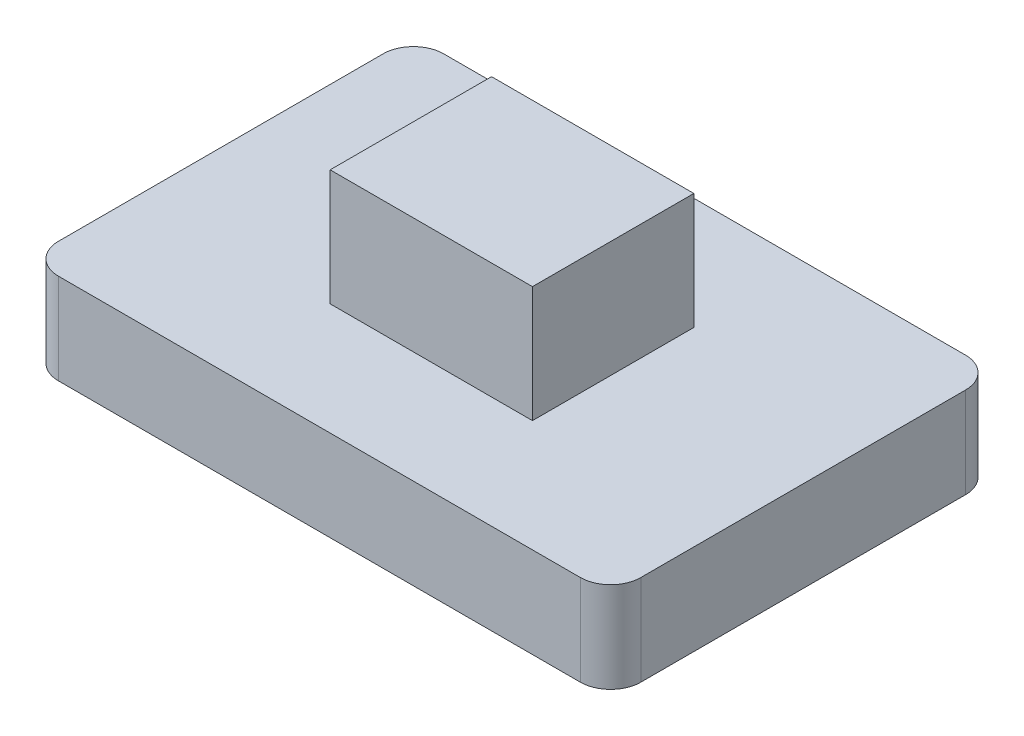
SolidWorks part; units mm, degrees
ref_plane "Front Plane" through (0, 0, 0) normal (0, 0, 1) x (1, 0, 0)
ref_plane "Top Plane" through (0, 0, 0) normal (0, 1, 0) x (1, 0, 0)
ref_plane "Right Plane" through (0, 0, 0) normal (1, 0, 0) x (0, 0, -1)
sketch "Sketch3" plane through (0, 0, 0) normal (0, 1, 0) x (1, 0, 0)
  line L1 (6.35, 0) -> (116.0039, 0)
  line L2 (0, 6.35) -> (0, 74.5793)
  line L3 (6.35, 80.9293) -> (116.0039, 80.9293)
  line L4 (122.3539, 6.35) -> (122.3539, 74.5793)
  arc A0 (6.35, 0) -> (0, 6.35) centre (6.35, 6.35) cw
  arc A1 (6.35, 80.9293) -> (0, 74.5793) centre (6.35, 74.5793) ccw
  arc A2 (122.3539, 74.5793) -> (116.0039, 80.9293) centre (116.0039, 74.5793) ccw
  arc A3 (122.3539, 6.35) -> (116.0039, 0) centre (116.0039, 6.35) cw
  point P7 (0, 0)
  dimension "D1" = 6.35
  dimension "D2" = 6.35
extrude "Extrude4" add sketch "Sketch3" against normal blind 19.05
sketch "Sketch4" plane through (0, 0, 0) normal (0, 1, 0) x (1, 0, 0)
  line L0 (0, 40.4646) -> (122.3539, 40.4646) construction
  line L1 (0, 74.5793) -> (0, 6.35) construction
  line L2 (122.3539, 6.35) -> (122.3539, 74.5793) construction
  line L4 (39.9244, 57.4189) -> (82.4295, 57.4189)
  line L5 (39.9244, 57.4189) -> (39.9244, 23.5103)
  line L6 (39.9244, 23.5103) -> (82.4295, 23.5103)
  line L7 (82.4295, 57.4189) -> (82.4295, 23.5103)
  point P6 (61.177, 40.4646)
extrude "Extrude5" add sketch "Sketch4" along normal blind 24.384
